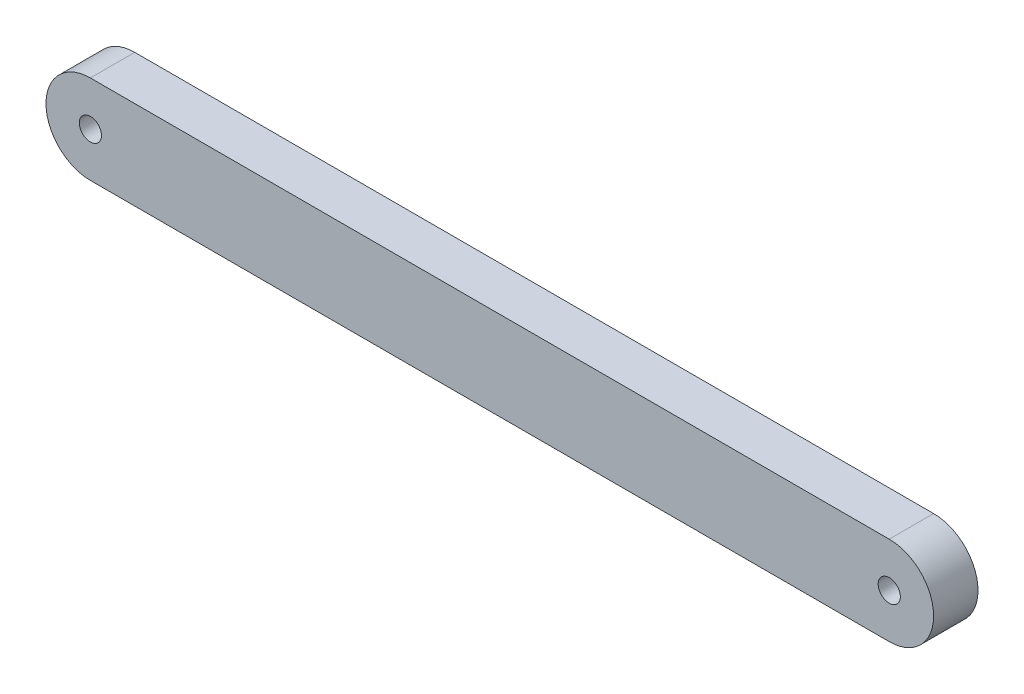
SolidWorks part; units mm, degrees
ref_plane "Front Plane" through (0, 0, 0) normal (0, 0, 1) x (1, 0, 0)
ref_plane "Top Plane" through (0, 0, 0) normal (0, 1, 0) x (1, 0, 0)
ref_plane "Right Plane" through (0, 0, 0) normal (1, 0, 0) x (0, 0, -1)
sketch "Sketch1" plane through (0, 0, 0) normal (0, 0, 1) x (1, 0, 0)
  line L0 (0, 10) -> (180, 10)
  line L1 (180, -10) -> (0, -10)
  circle A0 centre (0, 0) radius 2.5
  circle A1 centre (180, 0) radius 2.5
  arc A2 (0, -10) -> (0, 10) centre (0, 0) cw
  arc A3 (180, -10) -> (180, 10) centre (180, 0) ccw
  point P9 (-10, 0)
  dimension "D2" = 5
  dimension "D3" = 10
  dimension "D1" = 180
extrude "Boss-Extrude1" add sketch "Sketch1" along normal blind 10
